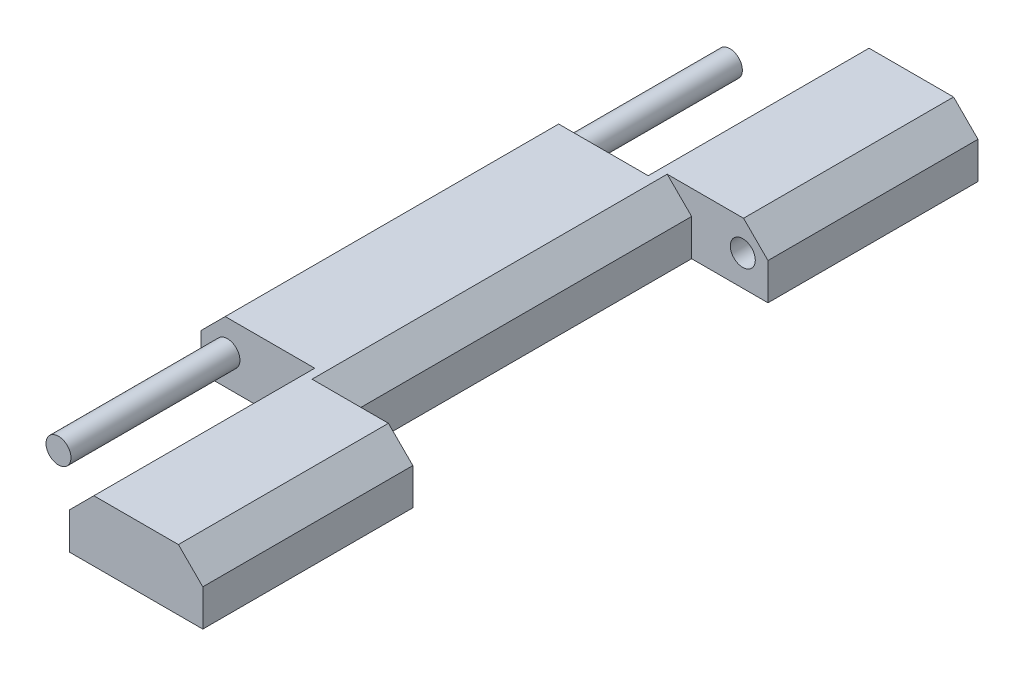
SolidWorks part; units mm, degrees
ref_plane "Front Plane" through (0, 0, 0) normal (0, 0, 1) x (1, 0, 0)
ref_plane "Top Plane" through (0, 0, 0) normal (0, 1, 0) x (1, 0, 0)
ref_plane "Right Plane" through (0, 0, 0) normal (1, 0, 0) x (0, 0, -1)
sketch "Sketch1" plane through (0, 0, 0) normal (0, 1, 0) x (1, 0, 0)
  line L0 (5.4621, -14.5454) -> (5.4621, -31.75)
  line L1 (-5.4621, 31.75) -> (5.4621, 31.75)
  line L2 (-5.4621, 31.75) -> (-5.4621, 13.6578)
  line L3 (-5.4621, -31.75) -> (5.4621, -31.75)
  line L4 (5.4621, 31.75) -> (5.4621, 14.5454)
  line L5 (-5.4621, -13.6578) -> (-5.4621, -31.75)
  line L7 (-12.7958, 13.6578) -> (-5.4621, 13.6578)
  line L8 (-12.7958, 13.6578) -> (-12.7958, -13.6578)
  line L9 (-12.7958, -13.6578) -> (-5.4621, -13.6578)
  line L13 (5.4621, -14.5454) -> (-0.7921, -14.5454)
  line L15 (5.4621, 14.5454) -> (-0.7921, 14.5454)
  line L16 (-0.7921, -14.5454) -> (-0.7921, 14.5454)
  point P0 (0, 0)
  point P6 (-7.9661, -1.326)
  point P12 (5.4621, 0)
  dimension "D1" = 63.5
extrude "Boss-Extrude1" add sketch "Sketch1" along normal blind 5
chamfer "Chamfer1" distance 2 angle 45 6 edges at (5.4621, 5, -23.1477) (-5.4621, 5, -22.7039) (-0.7921, 5, 0) (5.4621, 5, 23.1477) (-5.4621, 5, 22.7039) (-12.7958, 5, 0)
sketch "Sketch3" plane through (5.603, 0, 13.6578) normal (0, 0, 1) x (1, 0, 0)
  circle A0 centre (-16.2147, 2.5) radius 1.0217
ref_plane "Plane1" through (0, 0, 0) normal (0, 0, -1) x (-1, 0, 0)
extrude "Boss-Extrude2" add sketch "Sketch3" along normal mid plane 55 from surface at -13.6578 contours A0 starting at plane "Plane1"
pattern_linear "LPattern5" [suppressed] count 14 spacing 20
sketch "Sketch5" plane through (0, 0, -14.5454) normal (0, 0, 1) x (1, 0, 0)
  line L0 (-5.4621, 2.0622) -> (-0.7921, 2.0622)
  line L1 (-5.4621, 3) -> (-5.4621, 0) construction
  line L2 (-0.7921, 3) -> (-0.7921, 0) construction
  line L3 (-10.6117, 2.5) -> (-3.1271, 2.5)
  line L4 (-3.1271, 2.0622) -> (-3.1271, 2.5)
  line L5 (-3.1271, 2.5) -> (3.4003, 2.5)
  circle A0 centre (3.4003, 2.5) radius 1.0217
  circle A1 centre (-10.6117, 2.5) radius 1.0217 construction
extrude "Cut-Extrude1" cut sketch "Sketch5" against normal mid plane 55 from surface at 14.5454 contours A0 starting at plane "Plane1"
scale "Scale1" scale about centroid uniform scaling yes scale factor 1.35
